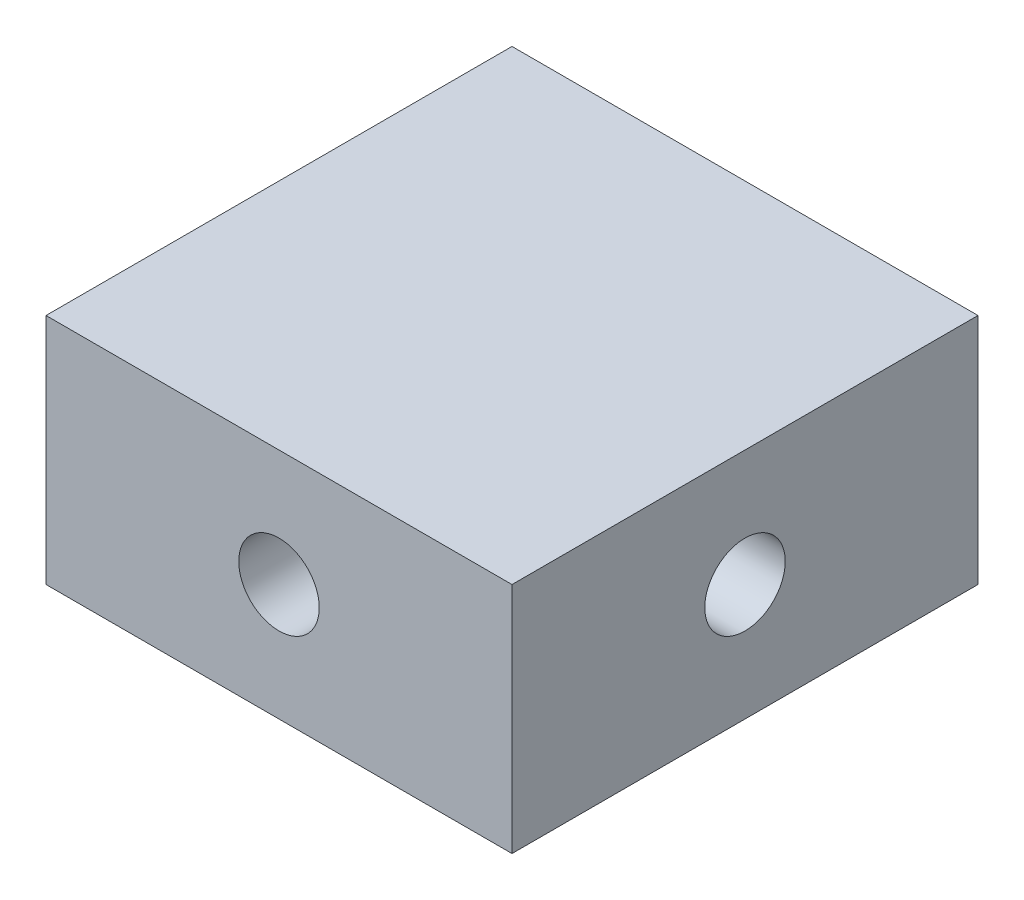
SolidWorks part; units mm, degrees
material "6061 Alloy"
ref_plane "Front Plane" through (0, 0, 0) normal (0, 0, 1) x (1, 0, 0)
ref_plane "Top Plane" through (0, 0, 0) normal (0, 1, 0) x (1, 0, 0)
ref_plane "Right Plane" through (0, 0, 0) normal (1, 0, 0) x (0, 0, -1)
sketch "Sketch1" plane through (0, 0, 0) normal (0, 1, 0) x (1, 0, 0)
  line L7 (-10, -10) -> (10, -10)
  line L8 (-10, -10) -> (-10, 10)
  line L9 (-10, 10) -> (10, 10)
  line L10 (10, -10) -> (10, 10)
  line L11 (-10, -10) -> (10, 10) construction
  line L12 (-10, 10) -> (10, -10) construction
  point P6 (0, 0)
  dimension "D1" = 20
  dimension "D2" = 20
extrude "Boss-Extrude1" add sketch "Sketch1" along normal mid plane 10
hole_wizard "#8-32 Tapped Hole1" positions "Sketch2" profile "Sketch3" tap size "#8-32" standard "ANSI Inch"
sketch "Sketch2" plane through (10, 0, 0) normal (1, 0, 0) x (0, 0, -1)
  point P0 (0, 0)
sketch "Sketch3" plane through (10, 0, 0) normal (0, 1, 0) x (0, 0, -1)
  line L0 (0, 0) -> (0, 7.3878)
  line L1 (0, 7.3878) -> (1.7272, 6.35)
  line L2 (1.7272, 6.35) -> (1.7272, 0)
  line L5 (1.7272, 0) -> (0, 0)
  line L10 (0, 7.3878) -> (-1.7272, 6.35) construction
  line L11 (0, -6.35) -> (0, 107.95) construction
  dimension "Tap Drill Dia." = 3.4544
  dimension "Tap Drill Depth" = 6.35
  dimension "Drill Angle" = 118
cosmetic thread "Hole Thread5" [suppressed] parameters "D1"=8.33, "D2"=4.4544
ref_axis "Axis1" through (0, 0, 0) along (0, 1, 0)
pattern_circular "CirPattern1" count 4 over 360 about axis through (0, 0, 0) along (0, 1, 0) of "#8-32 Tapped Hole1"
cosmetic thread "Hole Thread6" [suppressed] parameters "D1"=8.33, "D2"=4.4544
cosmetic thread "Hole Thread7" [suppressed] parameters "D1"=8.33, "D2"=4.4544
cosmetic thread "Hole Thread8" [suppressed] parameters "D1"=8.33, "D2"=4.4544
fillet "Fillet1" [suppressed] radius 5
